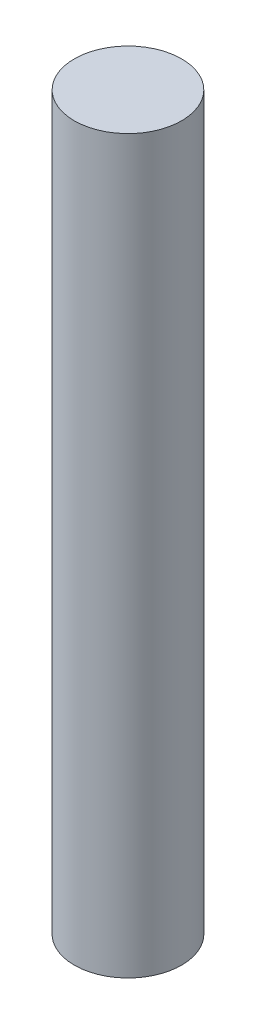
SolidWorks part; units mm, degrees
ref_plane "前视基准面" through (0, 0, 0) normal (0, 0, 1) x (1, 0, 0)
ref_plane "上视基准面" through (0, 0, 0) normal (0, 1, 0) x (1, 0, 0)
ref_plane "右视基准面" through (0, 0, 0) normal (1, 0, 0) x (0, 0, -1)
other "Configuration Table"
sketch "草图1" plane through (0, 0, 0) normal (0, 1, 0) x (1, 0, 0)
  circle A0 centre (0, 0) radius 35
  dimension "D1" = 70
extrude "凸台-拉伸1" add sketch "草图1" along normal blind 477
